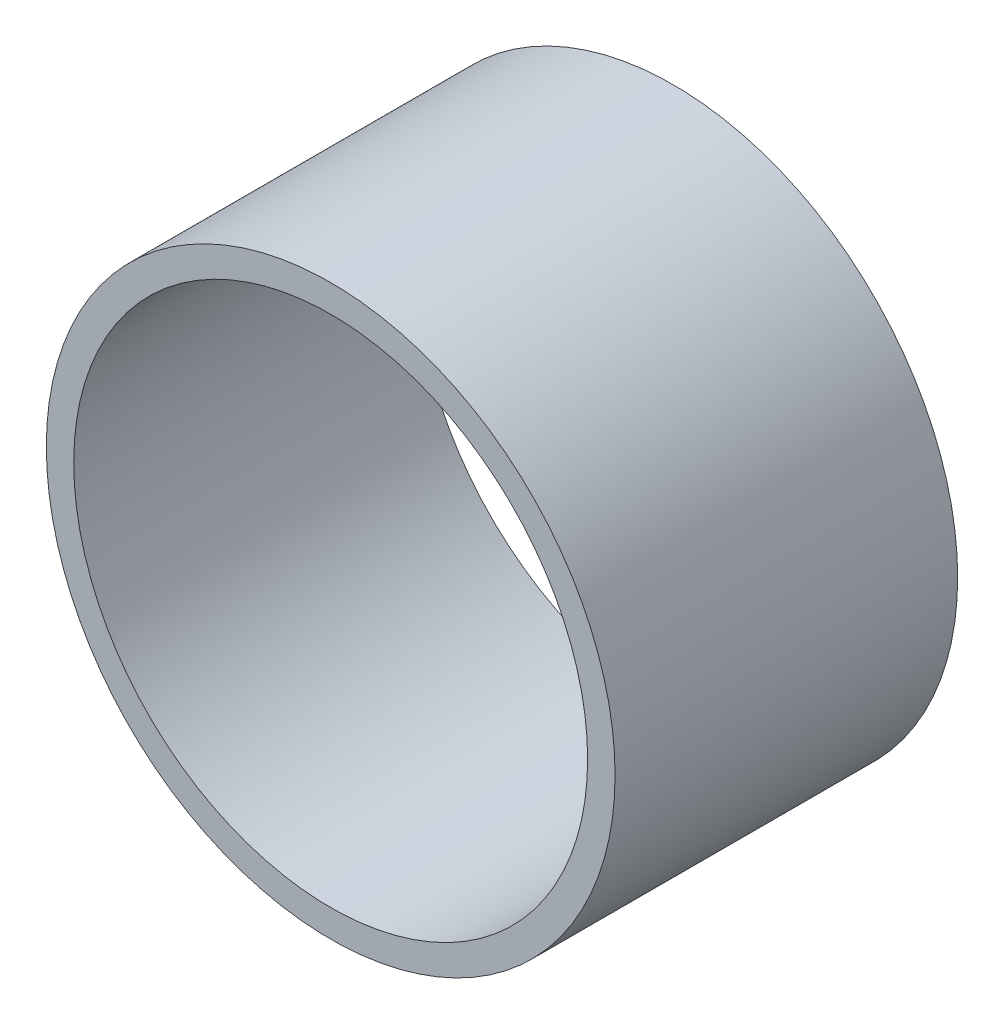
SolidWorks part; units mm, degrees
ref_plane "Front Plane" through (0, 0, 0) normal (0, 0, 1) x (1, 0, 0)
ref_plane "Top Plane" through (0, 0, 0) normal (0, 1, 0) x (1, 0, 0)
ref_plane "Right Plane" through (0, 0, 0) normal (1, 0, 0) x (0, 0, -1)
sketch "Sketch1" plane through (0, 0, 0) normal (0, 0, 1) x (1, 0, 0)
  circle A0 centre (0, 0) radius 0.375
  circle A1 centre (0, 0) radius 0.415
  dimension "D1" = 0.83
  dimension "D2" = 0.75
extrude "Boss-Extrude1" add sketch "Sketch1" along normal blind 0.5
